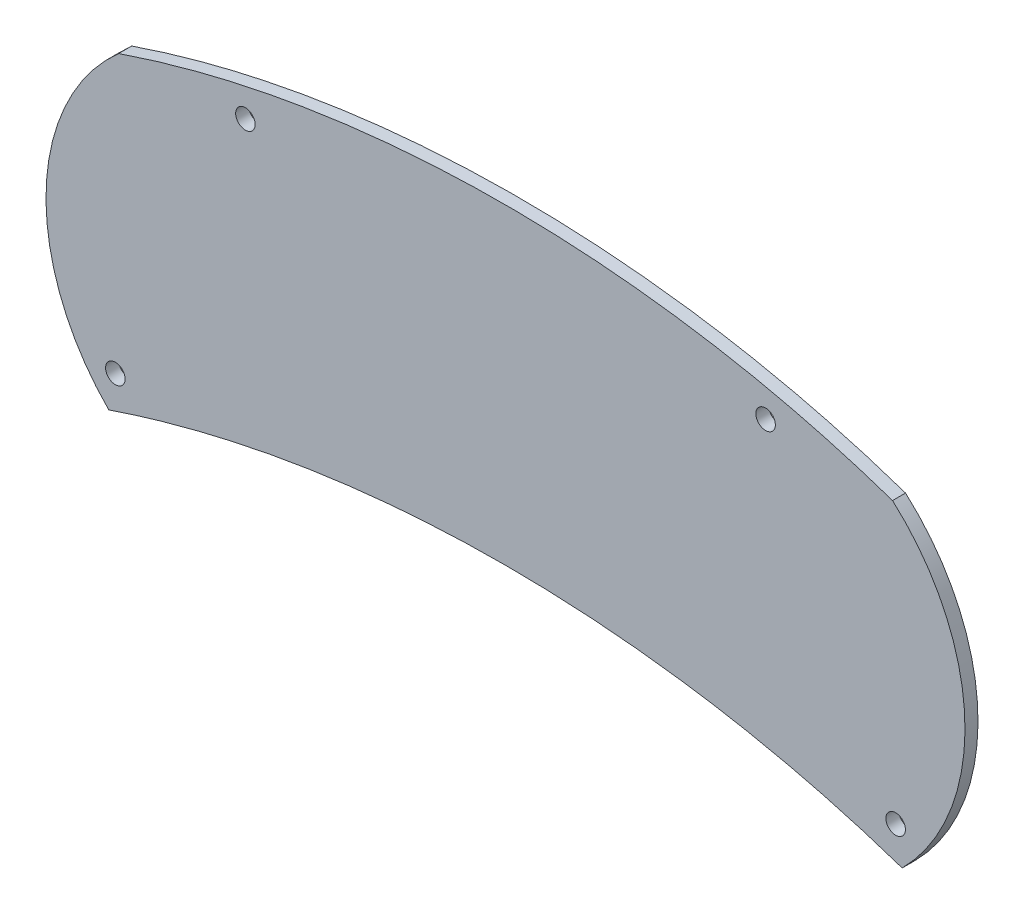
SolidWorks part; units mm, degrees
ref_plane "Alzado" through (0, 0, 0) normal (0, 0, 1) x (1, 0, 0)
ref_plane "Planta" through (0, 0, 0) normal (0, 1, 0) x (1, 0, 0)
ref_plane "Vista lateral" through (0, 0, 0) normal (1, 0, 0) x (0, 0, -1)
sketch "Croquis1" plane through (0, 0, 0) normal (0, 0, 1) x (-1, 0, 0)
  arc A8 (89.2306, -116.4483) -> (91.5105, -44.1084) centre (56.2541, -79.2031) ccw
  arc A9 (-91.5105, -44.1084) -> (-89.2827, -116.4022) centre (-56.2541, -79.2031) ccw
  circle A12 centre (90, -52.1509) radius 2.25
  circle A13 centre (60, -118) radius 2.25
  circle A14 centre (-60, -118) radius 2.25
  circle A15 centre (-90, -52.1509) radius 2.25
  spline S10 degree 3 poles (-89.2827, -116.4022) (-82.0844, -118.8711) (-74.8017, -120.9945) (-60.0822, -124.6121) (-52.6453, -126.1054) (-41.3796, -127.894) (-37.6141, -128.4132) (-30.0764, -129.3002) (-26.3022, -129.6681) (-14.9632, -130.5488) (-7.3824, -130.8398) (2.1203, -130.834) (4.0225, -130.8142) (7.8179, -130.7379) (13.5019, -130.5681) (19.1587, -130.2333) (30.4359, -129.3451) (37.9058, -128.4616) (52.7471, -126.0993) (60.1186, -124.6208) (74.7564, -121.0286) (82.0229, -118.9158) (89.2306, -116.4483) knots 0 0 0 0 0.125 0.125 0.25 0.25 0.3125 0.3125 0.375 0.375 0.5 0.5 0.53125 0.53125 0.5625 0.625 0.625 0.75 0.75 0.875 0.875 1 1 1 1
  spline S11 degree 3 poles (91.5105, -44.1084) (84.1278, -46.6265) (76.6598, -48.7936) (61.5677, -52.4855) (53.9436, -54.0102) (42.3954, -55.8359) (38.5347, -56.366) (30.8074, -57.2712) (26.9384, -57.6466) (15.3152, -58.5448) (7.545, -58.8406) (-2.1944, -58.8326) (-4.1446, -58.812) (-8.0363, -58.733) (-9.979, -58.6747) (-15.7977, -58.4434) (-19.6644, -58.2143) (-31.2272, -57.3029) (-38.8863, -56.3974) (-54.1032, -53.978) (-61.6612, -52.4642) (-76.6695, -48.7896) (-84.1199, -46.6291) (-91.5105, -44.1084) knots 0 0 0 0 0.125 0.125 0.25 0.25 0.3125 0.3125 0.375 0.375 0.5 0.5 0.53125 0.53125 0.5625 0.5625 0.625 0.625 0.75 0.75 0.875 0.875 1 1 1 1
extrude "Saliente-Extruir1" add sketch "Croquis1" along normal blind 3
